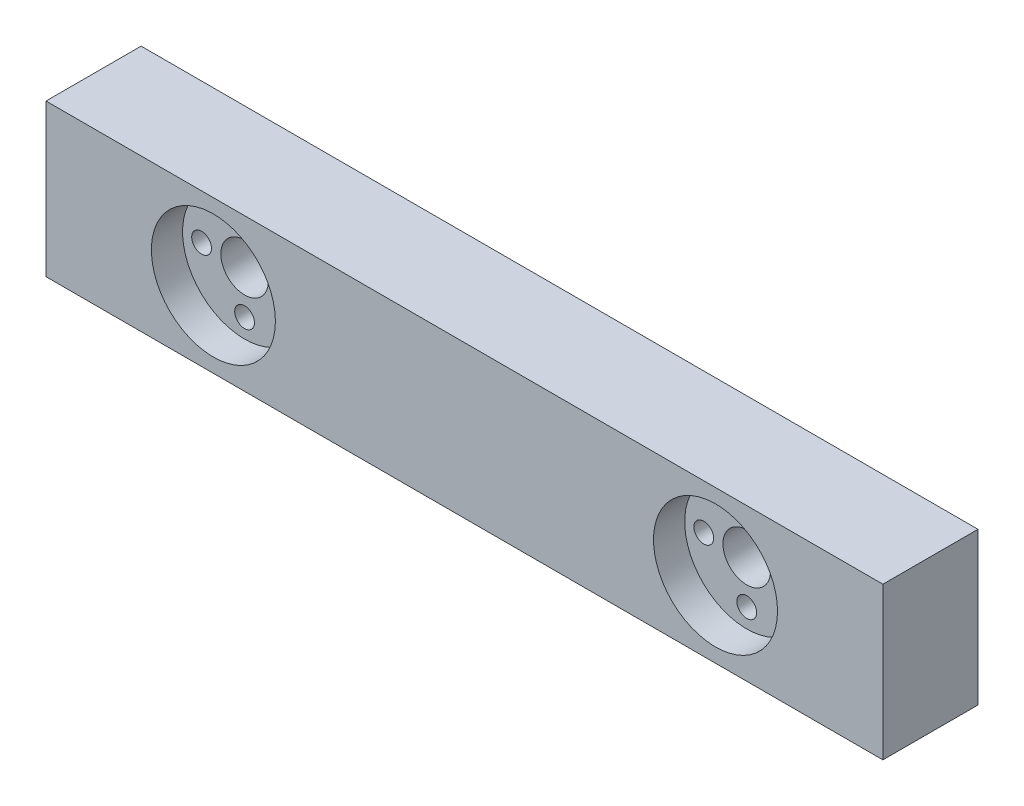
SolidWorks part; units mm, degrees
material "6061-T6 (SS)"
ref_plane "Front Plane" through (0, 0, 0) normal (0, 0, 1) x (1, 0, 0)
ref_plane "Top Plane" through (0, 0, 0) normal (0, 1, 0) x (1, 0, 0)
ref_plane "Right Plane" through (0, 0, 0) normal (1, 0, 0) x (0, 0, -1)
sketch "Sketch1" plane through (0, 0, 0) normal (0, 0, 1) x (1, 0, 0)
  line L1 (0, 0) -> (11000, 0)
  line L2 (0, 0) -> (0, 2000)
  line L3 (0, 2000) -> (11000, 2000)
  line L4 (11000, 0) -> (11000, 2000)
  dimension "D1" = 2000
  dimension "D2" = 11000
extrude "Boss-Extrude1" add sketch "Sketch1" against normal blind 1250
sketch "Sketch2" plane through (0, 0, 0) normal (0, 0, 1) x (1, 0, 0)
  line L1 (0, 0) -> (11000, 0) construction
  line L3 (0, 2000) -> (0, 0) construction
  line L4 (11000, 0) -> (11000, 2000) construction
  circle A0 centre (2200, 1000) radius 815
  circle A1 centre (8800, 1000) radius 815
  dimension "D1" = 1630
  dimension "D2" = 1630
  dimension "D3" = 1000
  dimension "D4" = 2200
  dimension "D5" = 2200
  dimension "D6" = 1000
extrude "Cut-Extrude2" cut sketch "Sketch2" against normal blind 410
sketch "Sketch23" plane through (0, 0, 0) normal (0, 0, 1) x (1, 0, 0)
  circle A0 centre (2200, 1000) radius 312.5
  circle A1 centre (8800, 1000) radius 312.5
  dimension "D1" = 625
  dimension "D2" = 625
extrude "Cut-Extrude3" cut sketch "Sketch23" against normal through all
sketch "Sketch24" plane through (0, 0, 0) normal (0, 0, 1) x (1, 0, 0)
  line L0 (2200, 1000) -> (2200, 435) construction
  line L1 (5500, 2000) -> (5500, 0) construction
  line L2 (11000, 2000) -> (0, 2000) construction
  line L3 (0, 0) -> (11000, 0) construction
  circle A0 centre (2200, 1000) radius 565 construction
  circle A1 centre (8800, 1000) radius 565 construction
  circle A2 centre (2200, 435) radius 130
  circle A3 centre (1635, 1000) radius 130
  circle A4 centre (2200, 1565) radius 130
  circle A5 centre (2765, 1000) radius 130
  dimension "D1" = 1130
  dimension "D2" = 1130
  dimension "D3" = 260
  dimension "D5" = 565
  dimension "D4" = 4
extrude "Cut-Extrude4" cut sketch "Sketch24" against normal through all
sketch "Sketch25" plane through (0, 0, 0) normal (0, 0, 1) x (1, 0, 0)
  line L0 (8800, 1000) -> (8800, 435) construction
  circle A0 centre (8800, 1000) radius 565 construction
  circle A1 centre (8800, 435) radius 130
  circle A2 centre (8235, 1000) radius 130
  circle A3 centre (8800, 1565) radius 130
  circle A4 centre (9365, 1000) radius 130
  dimension "D1" = 1130
  dimension "D2" = 260
  dimension "D4" = 565
  dimension "D3" = 4
extrude "Cut-Extrude5" cut sketch "Sketch25" against normal through all
scale "Scale1" scale about centroid uniform scaling yes scale factor 0.025
equation "\"Lenght\"= 11"
equation "\"Height\"= 2"
equation "\"Width\"= 1.25"
equation "\"D2@Sketch1\"=\"Lenght\""
equation "\"D1@Sketch1\"=\"Height\""
equation "\"D1@Boss-Extrude1\"=\"Width\""
equation "\"D3@Sketch2\"=\"Height\"/2"
equation "\"D4@Sketch2\"=\"Lenght\"*.20"
equation "\"D5@Sketch2\"=\"Lenght\"*.20"
equation "\"Depth\"= 0.41"
equation "\"D6@Sketch2\"=\"Height\"/2"
equation "\"Hole\"= 1.63"
equation "\"D2@Sketch2\"=\"Hole\""
equation "\"D1@Sketch2\"=\"Hole\""
equation "\"D1@Cut-Extrude2\"=\"Depth\""
equation "\"Mini Hole\"= 5 / 8"
equation "\"D1@Sketch23\"=\"Mini Hole\""
equation "\"D2@Sketch23\"=\"Mini Hole\""
